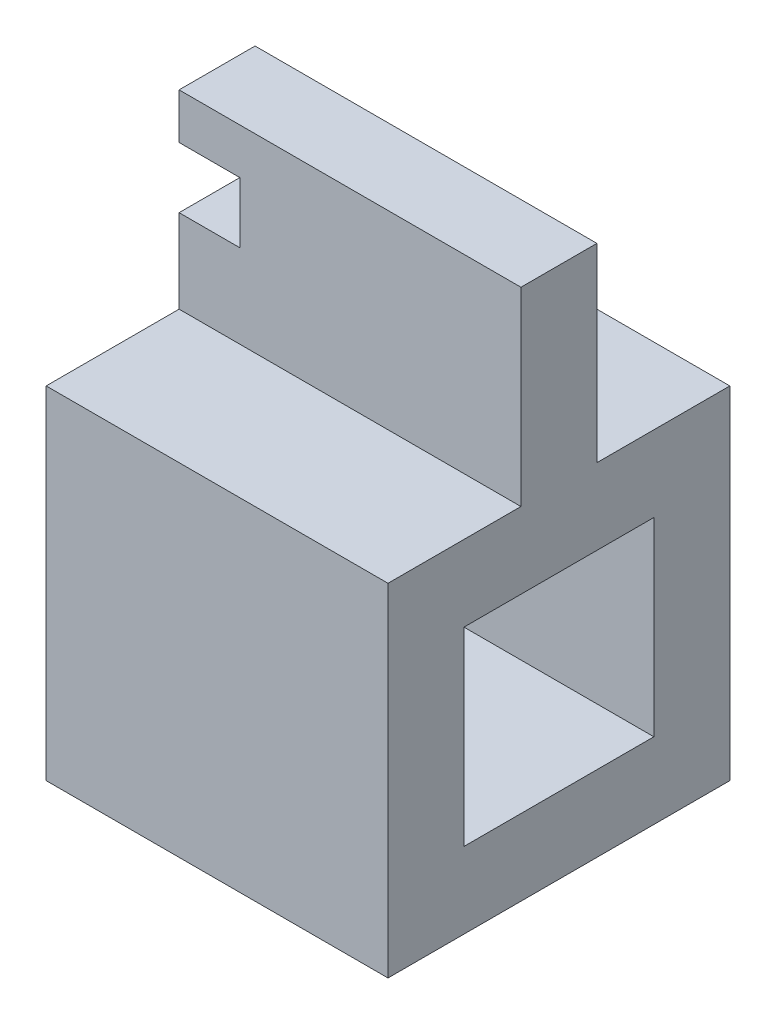
SolidWorks part; units mm, degrees
ref_plane "Front Plane" through (0, 0, 0) normal (0, 0, 1) x (1, 0, 0)
ref_plane "Top Plane" through (0, 0, 0) normal (0, 1, 0) x (1, 0, 0)
ref_plane "Right Plane" through (0, 0, 0) normal (1, 0, 0) x (0, 0, -1)
sketch "Sketch1" plane through (0, 0, 0) normal (1, 0, 0) x (0, 0, -1)
  line L1 (4.5, -4.5) -> (-4.5, -4.5)
  line L2 (4.5, -4.5) -> (4.5, 4.5)
  line L3 (4.5, 4.5) -> (-4.5, 4.5)
  line L4 (-4.5, -4.5) -> (-4.5, 4.5)
  line L5 (0, 4.5) -> (0, -4.5) construction
  line L6 (4.5, 0) -> (-4.5, 0) construction
  line L7 (2.5, -2.5) -> (-2.5, -2.5)
  line L8 (2.5, -2.5) -> (2.5, 2.5)
  line L9 (2.5, 2.5) -> (-2.5, 2.5)
  line L10 (-2.5, -2.5) -> (-2.5, 2.5)
  line L11 (0, 2.5) -> (0, -2.5) construction
  line L12 (2.5, 0) -> (-2.5, 0) construction
  point P0 (0, 0)
  point P4 (0, 0)
  dimension "D1" = 9
  dimension "D2" = 9
  dimension "D3" = 5
  dimension "D4" = 5
extrude "Boss-Extrude1" add sketch "Sketch1" along normal blind 9
sketch "Sketch2" plane through (0, 4.5, 0) normal (0, 1, 0) x (1, 0, 0)
  line L0 (0, 0) -> (9, 0) construction
  line L2 (9, -1) -> (0, -1)
  line L3 (9, -1) -> (9, 1)
  line L4 (0, 4.5) -> (0, -4.5)
  line L5 (0, -4.5) -> (9, -4.5)
  line L6 (9, -4.5) -> (9, 4.5)
  line L7 (9, 4.5) -> (0, 4.5)
  line L8 (0, 4.5) -> (0, -4.5)
  line L9 (0, -4.5) -> (9, -4.5)
  line L10 (9, -4.5) -> (9, 4.5)
  line L11 (9, 4.5) -> (0, 4.5)
  line L12 (9, 1) -> (0, 1)
  line L13 (0, -1) -> (0, 1)
  line L14 (4.5, 1) -> (4.5, -1) construction
  line L15 (9, 0) -> (0, 0) construction
  point P6 (4.5, 0)
  line M9 (9, -4.5) -> (9, 4.5)
  dimension "D2" = 2
  dimension "D1" = 0
extrude "Boss-Extrude2" add sketch "Sketch2" along normal blind 5 contours L12 L8 L2 M9
sketch "Sketch3" plane through (0, 0, 1) normal (0, 0, 1) x (1, 0, 0)
  line L0 (0, 8.3) -> (9, 8.3) construction
  line L2 (1.6, 6.7) -> (0, 6.7)
  line L3 (1.6, 6.7) -> (1.6, 8.3)
  line L4 (0, 4.5) -> (9, 4.5)
  line L5 (9, 4.5) -> (9, 9.5)
  line L6 (9, 9.5) -> (0, 9.5)
  line L7 (0, 9.5) -> (0, 4.5)
  line L8 (0, 4.5) -> (9, 4.5)
  line L9 (9, 4.5) -> (9, 9.5)
  line L10 (9, 9.5) -> (0, 9.5)
  line L11 (0, 9.5) -> (0, 4.5)
  line L12 (1.6, 8.3) -> (0, 8.3)
  line L13 (0, 6.7) -> (0, 8.3)
  line L14 (0.8, 8.3) -> (0.8, 6.7) construction
  line L15 (1.6, 7.5) -> (0, 7.5) construction
  point P6 (0.8, 7.5)
  dimension "D2" = 1.6
  dimension "D3" = 1.6
  dimension "D4" = 1.2
  dimension "D1" = 0
extrude "Cut-Extrude1" cut sketch "Sketch3" against normal blind 5 contours L3 L12 L11 L2
